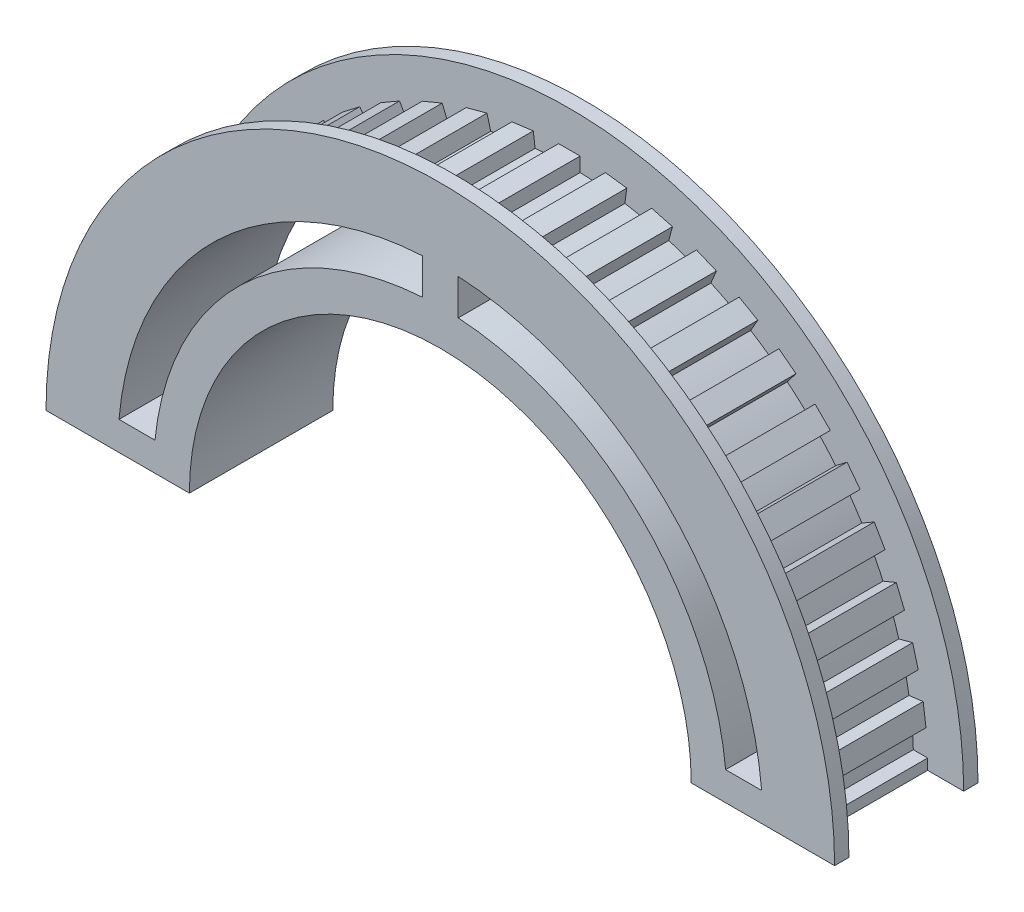
SolidWorks part; units mm, degrees
ref_plane "Front Plane" through (0, 0, 0) normal (0, 0, 1) x (1, 0, 0)
ref_plane "Top Plane" through (0, 0, 0) normal (0, 1, 0) x (1, 0, 0)
ref_plane "Right Plane" through (0, 0, 0) normal (1, 0, 0) x (0, 0, -1)
sketch "Sketch1" plane through (0, 0, 0) normal (0, 0, 1) x (1, 0, 0)
  line L0 (55, 0) -> (-55, 0) construction
  line L3 (-35, 0) -> (-40, 0)
  line L4 (35, 0) -> (40, 0)
  line L5 (0, -55) -> (0, 55) construction
  line L10 (-45.7995, 0) -> (-39.7995, 0)
  line L11 (-45.7995, 0) -> (-45.7995, 4)
  line L12 (-45.7995, 4) -> (-39.7995, 4)
  line L13 (-39.7995, 0) -> (-39.7995, 4)
  line L14 (39.7995, 0) -> (45.7995, 0)
  line L15 (39.7995, 0) -> (39.7995, 4)
  line L16 (39.7995, 4) -> (45.7995, 4)
  line L17 (45.7995, 0) -> (45.7995, 4)
  line L18 (-2.5, 39.9218) -> (2.5, 39.9218)
  line L19 (-2.5, 39.9218) -> (-2.5, 45.9218)
  line L20 (-2.5, 45.9218) -> (2.5, 45.9218)
  line L21 (2.5, 39.9218) -> (2.5, 45.9218)
  line L22 (-45, 0) -> (-48, 0)
  line L23 (45, 0) -> (48, 0)
  line L24 (4.775, 47.7619) -> (5.0361, 49.7448)
  line L29 (-1.5, 47.9766) -> (1.5, 47.9766)
  line L30 (-1.5, 47.9766) -> (-1.5, 49.9766)
  line L31 (-1.5, 49.9766) -> (1.5, 49.9766)
  line L32 (1.5, 47.9766) -> (1.5, 49.9766)
  line L33 (4.775, 47.7619) -> (7.7494, 47.3703)
  line L34 (7.7494, 47.3703) -> (8.0104, 49.3532)
  line L35 (5.0361, 49.7448) -> (8.0104, 49.3532)
  line L36 (10.9684, 46.73) -> (11.486, 48.6619)
  line L37 (10.9684, 46.73) -> (13.8661, 45.9536)
  line L38 (13.8661, 45.9536) -> (14.3838, 47.8854)
  line L39 (11.486, 48.6619) -> (14.3838, 47.8854)
  line L40 (16.974, 44.8986) -> (17.7394, 46.7463)
  line L41 (16.974, 44.8986) -> (19.7457, 43.7505)
  line L42 (19.7457, 43.7505) -> (20.511, 45.5983)
  line L43 (17.7394, 46.7463) -> (20.511, 45.5983)
  line L44 (22.6892, 42.2989) -> (23.6892, 44.031)
  line L45 (22.6892, 42.2989) -> (25.2873, 40.7989)
  line L46 (25.2873, 40.7989) -> (26.2873, 42.531)
  line L47 (23.6892, 44.031) -> (26.2873, 42.531)
  line L48 (28.0162, 38.9755) -> (29.2338, 40.5622)
  line L49 (28.0162, 38.9755) -> (30.3963, 37.1492)
  line L50 (30.3963, 37.1492) -> (31.6138, 38.7359)
  line L51 (29.2338, 40.5622) -> (31.6138, 38.7359)
  line L52 (32.8639, 34.9852) -> (34.2781, 36.3994)
  line L53 (32.8639, 34.9852) -> (34.9852, 32.8639)
  line L54 (34.9852, 32.8639) -> (36.3994, 34.2781)
  line L55 (34.2781, 36.3994) -> (36.3994, 34.2781)
  line L56 (37.1492, 30.3963) -> (38.7359, 31.6138)
  line L57 (37.1492, 30.3963) -> (38.9755, 28.0162)
  line L58 (38.9755, 28.0162) -> (40.5622, 29.2338)
  line L59 (38.7359, 31.6138) -> (40.5622, 29.2338)
  line L60 (40.7989, 25.2873) -> (42.531, 26.2873)
  line L61 (40.7989, 25.2873) -> (42.2989, 22.6892)
  line L62 (42.2989, 22.6892) -> (44.031, 23.6892)
  line L63 (42.531, 26.2873) -> (44.031, 23.6892)
  line L64 (43.7505, 19.7457) -> (45.5983, 20.511)
  line L65 (43.7505, 19.7457) -> (44.8986, 16.974)
  line L66 (44.8986, 16.974) -> (46.7463, 17.7394)
  line L67 (45.5983, 20.511) -> (46.7463, 17.7394)
  line L68 (45.9536, 13.8661) -> (47.8854, 14.3838)
  line L69 (45.9536, 13.8661) -> (46.73, 10.9684)
  line L70 (46.73, 10.9684) -> (48.6619, 11.486)
  line L71 (47.8854, 14.3838) -> (48.6619, 11.486)
  line L72 (47.3703, 7.7494) -> (49.3532, 8.0104)
  line L73 (47.3703, 7.7494) -> (47.7619, 4.775)
  line L74 (47.7619, 4.775) -> (49.7448, 5.0361)
  line L75 (49.3532, 8.0104) -> (49.7448, 5.0361)
  line L80 (-7.7494, 47.3703) -> (-8.0104, 49.3532)
  line L81 (-7.7494, 47.3703) -> (-4.775, 47.7619)
  line L82 (-4.775, 47.7619) -> (-5.0361, 49.7448)
  line L83 (-8.0104, 49.3532) -> (-5.0361, 49.7448)
  line L84 (-13.8661, 45.9536) -> (-14.3838, 47.8854)
  line L85 (-13.8661, 45.9536) -> (-10.9684, 46.73)
  line L86 (-10.9684, 46.73) -> (-11.486, 48.6619)
  line L87 (-14.3838, 47.8854) -> (-11.486, 48.6619)
  line L88 (-19.7457, 43.7505) -> (-20.511, 45.5983)
  line L89 (-19.7457, 43.7505) -> (-16.974, 44.8986)
  line L90 (-16.974, 44.8986) -> (-17.7394, 46.7463)
  line L91 (-20.511, 45.5983) -> (-17.7394, 46.7463)
  line L92 (-25.2873, 40.7989) -> (-26.2873, 42.531)
  line L93 (-25.2873, 40.7989) -> (-22.6892, 42.2989)
  line L94 (-22.6892, 42.2989) -> (-23.6892, 44.031)
  line L95 (-26.2873, 42.531) -> (-23.6892, 44.031)
  line L96 (-30.3963, 37.1492) -> (-31.6138, 38.7359)
  line L97 (-30.3963, 37.1492) -> (-28.0162, 38.9755)
  line L98 (-28.0162, 38.9755) -> (-29.2338, 40.5622)
  line L99 (-31.6138, 38.7359) -> (-29.2338, 40.5622)
  line L100 (-34.9852, 32.8639) -> (-36.3994, 34.2781)
  line L101 (-34.9852, 32.8639) -> (-32.8639, 34.9852)
  line L102 (-32.8639, 34.9852) -> (-34.2781, 36.3994)
  line L103 (-36.3994, 34.2781) -> (-34.2781, 36.3994)
  line L104 (-38.9755, 28.0162) -> (-40.5622, 29.2338)
  line L105 (-38.9755, 28.0162) -> (-37.1492, 30.3963)
  line L106 (-37.1492, 30.3963) -> (-38.7359, 31.6138)
  line L107 (-40.5622, 29.2338) -> (-38.7359, 31.6138)
  line L108 (-42.2989, 22.6892) -> (-44.031, 23.6892)
  line L109 (-42.2989, 22.6892) -> (-40.7989, 25.2873)
  line L110 (-40.7989, 25.2873) -> (-42.531, 26.2873)
  line L111 (-44.031, 23.6892) -> (-42.531, 26.2873)
  line L112 (-44.8986, 16.974) -> (-46.7463, 17.7394)
  line L113 (-44.8986, 16.974) -> (-43.7505, 19.7457)
  line L114 (-43.7505, 19.7457) -> (-45.5983, 20.511)
  line L115 (-46.7463, 17.7394) -> (-45.5983, 20.511)
  line L116 (-46.73, 10.9684) -> (-48.6619, 11.486)
  line L117 (-46.73, 10.9684) -> (-45.9536, 13.8661)
  line L118 (-45.9536, 13.8661) -> (-47.8854, 14.3838)
  line L119 (-48.6619, 11.486) -> (-47.8854, 14.3838)
  line L120 (-47.7619, 4.775) -> (-49.7448, 5.0361)
  line L121 (-47.7619, 4.775) -> (-47.3703, 7.7494)
  line L122 (-47.3703, 7.7494) -> (-49.3532, 8.0104)
  line L123 (-49.7448, 5.0361) -> (-49.3532, 8.0104)
  line L128 (-47.9766, -1.5) -> (-49.9766, -1.5) [skipped]
  line L129 (-49.9766, -1.5) -> (-49.9766, 1.5) [skipped]
  line L130 (-47.9766, 1.5) -> (-49.9766, 1.5) [skipped]
  line L131 (-47.9766, -1.5) -> (-47.9766, 1.5) [skipped]
  line L132 (47.9766, 1.5) -> (49.9766, 1.5) [skipped]
  line L133 (49.9766, 1.5) -> (49.9766, -1.5) [skipped]
  line L134 (47.9766, -1.5) -> (49.9766, -1.5) [skipped]
  line L135 (47.9766, 1.5) -> (47.9766, -1.5) [skipped]
  line L137 (47.9766, 1.5) -> (49.9766, 1.5)
  line L138 (47.9766, 1.5) -> (47.9766, 0)
  line L139 (47.9766, 0) -> (49.9766, 0)
  line L140 (49.9766, 1.5) -> (49.9766, 0)
  line L141 (-47.9766, 1.5) -> (-49.9766, 1.5)
  line L142 (-47.9766, 1.5) -> (-47.9766, 0)
  line L143 (-47.9766, 0) -> (-49.9766, 0)
  line L144 (-49.9766, 1.5) -> (-49.9766, 0)
  arc A2 (-35, 0) -> (35, 0) centre (0, 0) cw
  arc A3 (-40, 0) -> (40, 0) centre (0, 0) cw
  arc A4 (45, 0) -> (-45, 0) centre (0, 0) ccw
  arc A5 (48, 0) -> (-48, 0) centre (0, 0) ccw
  point P81 (0, 0)
  point P131 (0, 0)
  dimension "D4" = 6
  dimension "D5" = 35
  dimension "D8" = 40
  dimension "D15" = 2
  dimension "D3" = 48
  dimension "D2" = 3
  dimension "D6" = 5
  dimension "D7" = 5
  dimension "D9" = 4
  dimension "D10" = 4
  dimension "D11" = 5
  dimension "D12" = 2.5
  dimension "D13" = 6
  dimension "D14" = 6
  dimension "D16" = 3
  dimension "D17" = 1.5
  dimension "D20" = 1.5
  dimension "D21" = 2
  dimension "D22" = 2
  dimension "D23" = 1.5
  dimension "D18" = 13
  dimension "D19" = 13
extrude "Boss-Extrude1" add sketch "Sketch1" along normal blind 20
sketch "Sketch3" plane through (0, 0, 0) normal (0, -1, 0) x (1, 0, 0)
  line L0 (-35, 20) -> (-35, 0) construction
  line L2 (-35, 20) -> (-49.9766, 20) construction
  circle A0 centre (-42.5, 10) radius 1.5
  dimension "D1" = 3
  dimension "D2" = 7.5
  dimension "D4" = 10
extrude "Cut-Extrude2" cut sketch "Sketch3" against normal up to next
mirror "Mirror2" about plane through (0, 0, 0) normal (1, 0, 0) of "Cut-Extrude2"
sketch "Sketch5" plane through (0, 0, 0) normal (0, 0, 1) x (1, 0, 0)
  line L0 (55, 0) -> (-55, 0) construction
  line L1 (-48, 0) -> (-55, 0)
  line L2 (48, 0) -> (55, 0)
  arc A0 (48, 0) -> (-48, 0) centre (0, 0) ccw
  circle A1 centre (0, 0) radius 48 construction
  arc A2 (55, 0) -> (-55, 0) centre (0, 0) ccw
  dimension "D1" = 55
  dimension "D2" = 7
extrude "Boss-Extrude3" add sketch "Sketch5" along normal blind 2
sketch "Sketch6" plane through (0, 0, 20) normal (0, 0, 1) x (1, 0, 0)
  line L0 (11, 0) -> (-11, 0) construction
  line L1 (-45, 0) -> (-55, 0)
  line L2 (45, 0) -> (55, 0)
  arc A0 (55, 0) -> (-55, 0) centre (0, 0) ccw
  arc A1 (45, 0) -> (-45, 0) centre (0, 0) ccw
  dimension "D1" = 55
  dimension "D2" = 45
extrude "Boss-Extrude4" add sketch "Sketch6" against normal blind 2
